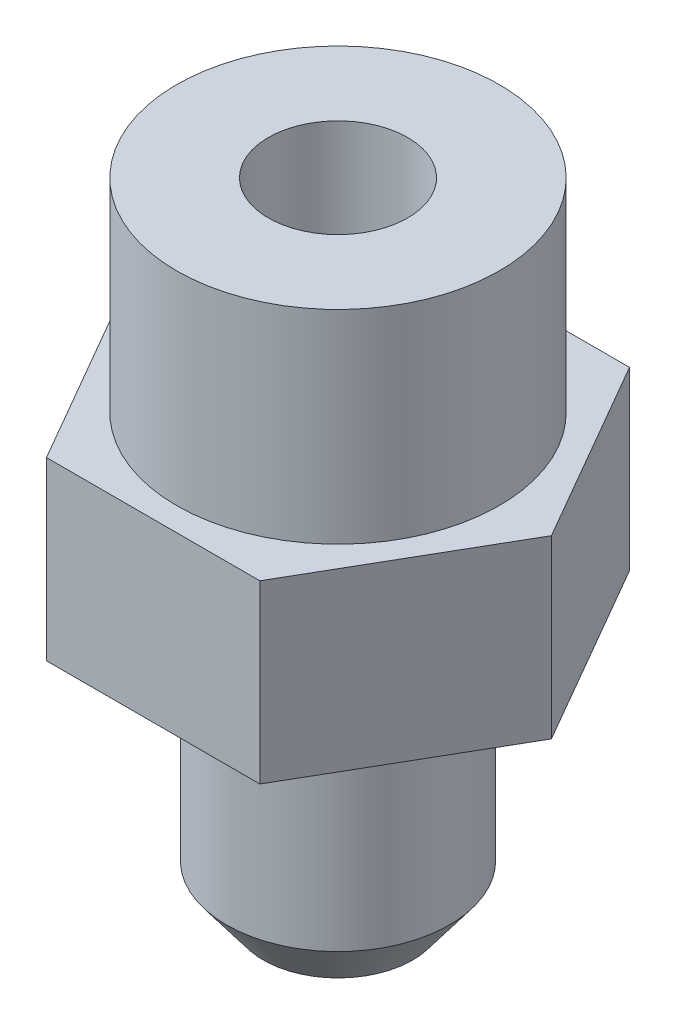
SolidWorks part; units mm, degrees
material "6061-T6 (SS)"
ref_plane "Front Plane" through (0, 0, 0) normal (0, 0, 1) x (1, 0, 0)
ref_plane "Top Plane" through (0, 0, 0) normal (0, 1, 0) x (1, 0, 0)
ref_plane "Right Plane" through (0, 0, 0) normal (1, 0, 0) x (0, 0, -1)
sketch "Sketch1" plane through (0, 0, 0) normal (0, 1, 0) x (1, 0, 0)
  circle A0 centre (0, 0) radius 8.7312
  dimension "D1" = 17.4625
extrude "Boss-Extrude1" add sketch "Sketch1" along normal blind 11
sketch "Sketch2" plane through (0, 0, 0) normal (0, -1, 0) x (1, 0, 0)
  line L1 (-11.5484, 0) -> (-5.7742, -10.0012)
  line L2 (-5.7742, -10.0012) -> (5.7742, -10.0013)
  line L3 (5.7742, -10.0013) -> (11.5484, 0)
  line L4 (11.5484, 0) -> (5.7742, 10.0013)
  line L5 (5.7742, 10.0013) -> (-5.7742, 10.0013)
  line L6 (-5.7742, 10.0013) -> (-11.5484, 0)
  circle A0 centre (0, 0) radius 10.0012 construction
  circle A1 centre (0, 0) radius 8.7312 construction
  dimension "D1" = 1.27
extrude "Boss-Extrude2" add sketch "Sketch2" along normal blind 9.525
sketch "Sketch3" plane through (0, -9.525, 0) normal (0, -1, 0) x (1, 0, 0)
  circle A0 centre (0, 0) radius 6.0325
  dimension "D1" = 12.065
extrude "Boss-Extrude3" add sketch "Sketch3" along normal blind 14.1224
sketch "Sketch4" plane through (0, -23.6474, 0) normal (0, -1, 0) x (1, 0, 0)
  circle A0 centre (0, 0) radius 13.2439
  circle A1 centre (0, 0) radius 4.0386
  dimension "D1" = 8.0772
extrude "Cut-Extrude1" cut sketch "Sketch4" against normal through all draft 37
sketch "Sketch5" plane through (0, -23.6474, 0) normal (0, -1, 0) x (1, 0, 0)
  circle A0 centre (0, 0) radius 3.7719
  dimension "D1" = 7.5438
extrude "Cut-Extrude2" cut sketch "Sketch5" against normal through all
